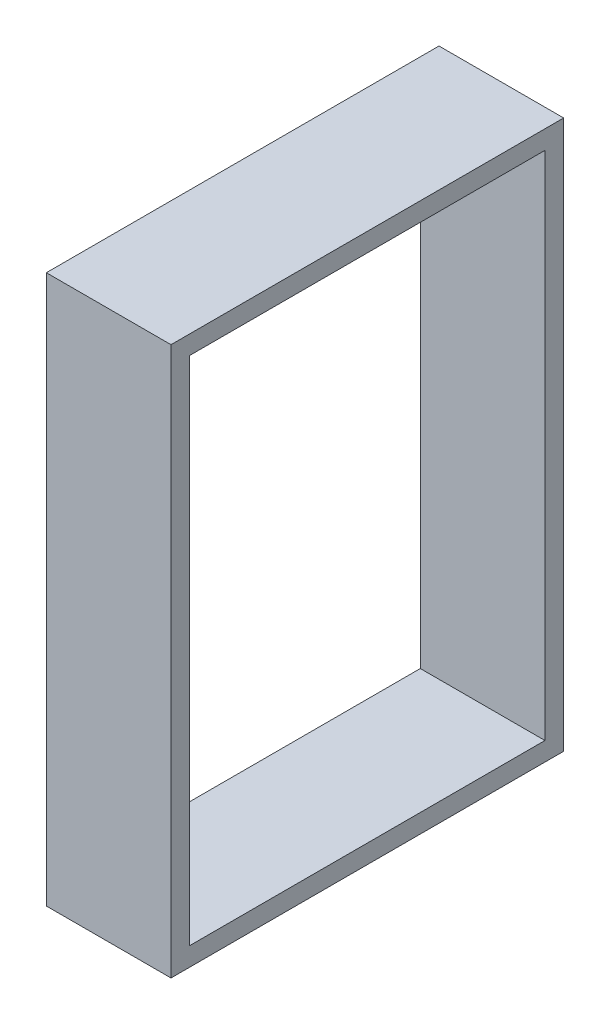
SolidWorks part; units mm, degrees
other "Battery Strap Right 1"
ref_plane "Front Plane" through (0, 0, 0) normal (0, 0, 1) x (1, 0, 0)
ref_plane "Top Plane" through (0, 0, 0) normal (0, 1, 0) x (1, 0, 0)
ref_plane "Right Plane" through (0, 0, 0) normal (1, 0, 0) x (0, 0, -1)
sketch3d "Main Profile Sketch datum points"
  point P0 (-240, 0, 0)
  point P1 (-240, 10, 0)
  point P2 (-240, 0, 10)
ref_plane "Main Profile Sketch plane" through (-240, 0, 0) normal (1, 0, 0) x (0, 0, -1)
sketch "Main Profile Sketch" plane through (-240, 0, 0) normal (1, 0, 0) x (0, 0, -1)
  line L0 (-80, -48.5) -> (-80, -4.5)
  line L1 (-80, -4.5) -> (-48.5, -4.5)
  line L2 (-48.5, -48.5) -> (-48.5, -4.5)
  line L3 (-80, -48.5) -> (-48.5, -48.5)
  line L4 (-50, -47) -> (-50, -6)
  line L5 (-78.5, -6) -> (-50, -6)
  line L6 (-78.5, -47) -> (-78.5, -6)
  line L7 (-78.5, -47) -> (-50, -47)
extrude "Main Extrusion" add sketch "Main Profile Sketch" against normal blind 10 separate body
